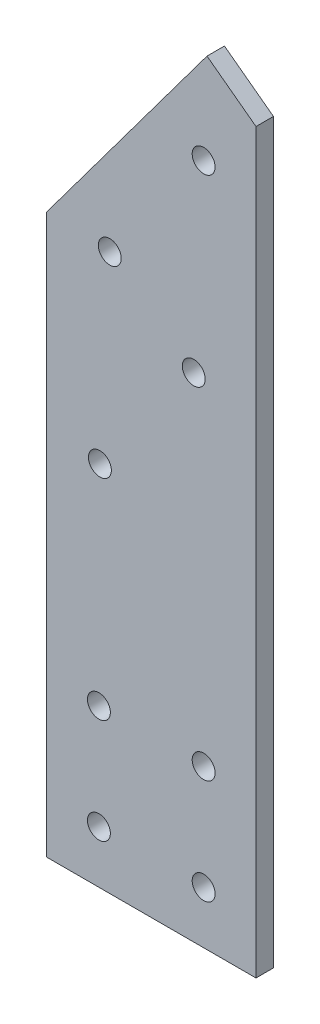
SolidWorks part; units mm, degrees
material "6061-T6 (SS)"
ref_plane "Front" through (0, 0, 0) normal (0, 0, 1) x (1, 0, 0)
ref_plane "Top" through (0, 0, 0) normal (0, 1, 0) x (1, 0, 0)
ref_plane "Right" through (0, 0, 0) normal (1, 0, 0) x (0, 0, -1)
sketch "Sketch2" plane through (0, 0, 0) normal (0, 0, 1) x (1, 0, 0)
  line L0 (0, 0) -> (76.2, 0)
  line L1 (0, 0) -> (0, 203.2)
  line L2 (0, 203.2) -> (58.3782, 281.5489)
  line L3 (76.2, 268.2698) -> (76.2, 0)
  line L4 (58.3782, 281.5489) -> (76.2, 268.2698)
  dimension "D1" = 76.2
  dimension "D2" = 203.2
  dimension "D3" = 53.31
  dimension "D4" = 22.225
extrude "Boss-Extrude1" add sketch "Sketch2" along normal blind 6.35
hole_wizard "21/64 (0.32813) Diameter Hole1" positions "Sketch3" profile "Sketch4" hole size "21/64" standard "ANSI Inch" end condition through all
sketch "Sketch3" plane through (0, 0, 6.35) normal (0, 0, 1) x (1, 0, 0)
  line L0 (76.2, 0) -> (76.2, 268.2698) construction
  line L1 (0, 0) -> (76.2, 0) construction
  point P0 (57.15, 19.05)
  dimension "D1" = 19.05
  dimension "D2" = 19.05
sketch "Sketch4" plane through (57.15, 19.05, 6.35) normal (1, 0, 0) x (0, -1, 0)
  line L0 (0, 0) -> (0, 6.35)
  line L1 (0, 6.35) -> (4.1673, 6.35)
  line L2 (4.1673, 6.35) -> (4.1673, 0)
  line L5 (4.1673, 0) -> (0, 0)
  line L11 (0, -6.35) -> (0, 107.95) construction
  dimension "Thru Hole Dia." = 8.3345
  dimension "Thru Hole Depth" = 6.35
pattern_linear "LPattern1" count 2 spacing 38.1 along (-1, 0, 0) count 2 spacing 38.1 along (0, 1, 0) of "21/64 (0.32813) Diameter Hole1"
hole_wizard "21/64 (0.32813) Diameter Hole2" positions "Sketch5" profile "Sketch6" hole size "21/64" standard "ANSI Inch" end condition through all
sketch "Sketch5" plane through (0, 0, 6.35) normal (0, 0, 1) x (1, 0, 0)
  line L0 (76.2, 0) -> (76.2, 268.2698) construction
  line L1 (58.3782, 281.5489) -> (0, 203.2) construction
  point P0 (57.15, 248.0169)
  dimension "D1" = 19.05
  dimension "D2" = 19.05
sketch "Sketch6" plane through (57.15, 248.0169, 6.35) normal (1, 0, 0) x (0, -1, 0)
  line L0 (0, 0) -> (0, 6.35)
  line L1 (0, 6.35) -> (4.1673, 6.35)
  line L2 (4.1673, 6.35) -> (4.1673, 0)
  line L5 (4.1673, 0) -> (0, 0)
  line L11 (0, -6.35) -> (0, 107.95) construction
  dimension "Thru Hole Dia." = 8.3345
  dimension "Thru Hole Depth" = 6.35
pattern_linear "LPattern2" count 3 spacing 57.15 along (-0.5975, -0.8019, 0) count 2 spacing 38.1 along (0.8019, -0.5975, 0) skipping (0, 1), (2, 0) of "21/64 (0.32813) Diameter Hole2"
